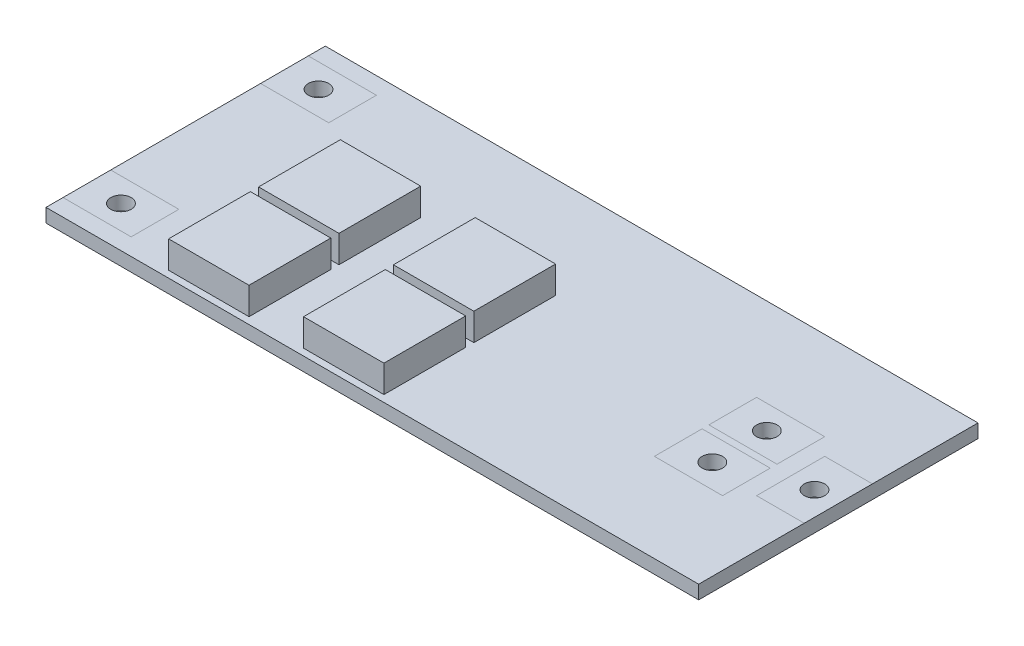
SolidWorks part; units mm, degrees
ref_plane "Alzado" through (0, 0, 0) normal (0, 0, 1) x (1, 0, 0)
ref_plane "Planta" through (0, 0, 0) normal (0, 1, 0) x (1, 0, 0)
ref_plane "Vista lateral" through (0, 0, 0) normal (1, 0, 0) x (0, 0, -1)
sketch "Croquis1" plane through (0, 0, 0) normal (0, 1, 0) x (1, 0, 0)
  line L0 (23.95, 0) -> (-23.95, 0) construction
  line L1 (-23.95, 10.25) -> (23.95, 10.25)
  line L2 (-23.95, 10.25) -> (-23.95, -10.25)
  line L3 (-23.95, -10.25) -> (23.95, -10.25)
  line L4 (23.95, 10.25) -> (23.95, -10.25)
  line L5 (-23.95, 10.25) -> (23.95, -10.25) construction
  line L6 (-23.95, -10.25) -> (23.95, 10.25) construction
  circle A0 centre (22.2, 0) radius 0.75
  circle A1 centre (16.7, 2) radius 0.75
  circle A2 centre (-21.45, 7.25) radius 0.75
  circle A3 centre (16.7, -2) radius 0.75
  circle A4 centre (-21.45, -7.25) radius 0.75
  point P0 (0, 0)
  point P10 (22.95, 0)
  point P13 (0, 0)
  dimension "D4" = 1.5
  dimension "D1" = 47.9
  dimension "D2" = 20.5
  dimension "D3" = 1
  dimension "D5" = 5.5
  dimension "D6" = 2
  dimension "D7" = 2.5
  dimension "D8" = 3
extrude "Saliente-Extruir1" add sketch "Croquis1" along normal blind 1
sketch "Croquis2" plane through (0, 1, 0) normal (0, 1, 0) x (1, 0, 0)
  line L0 (-7.55, -10.25) -> (-7.55, 10.25) construction
  line L1 (-15.45, 2.85) -> (-9.55, 2.85)
  line L2 (-15.45, 2.85) -> (-15.45, -3.15)
  line L3 (-15.45, -3.15) -> (-9.55, -3.15)
  line L4 (-9.55, 2.85) -> (-9.55, -3.15)
  line L5 (-15.45, -3.75) -> (-9.55, -3.75)
  line L6 (-15.45, -3.75) -> (-15.45, -9.75)
  line L7 (-15.45, -9.75) -> (-9.55, -9.75)
  line L8 (-9.55, -3.75) -> (-9.55, -9.75)
  line L9 (-23.95, -10.25) -> (23.95, -10.25) construction
  line L10 (23.95, 10.25) -> (-23.95, 10.25) construction
  line L11 (-23.95, 10.25) -> (-23.95, -10.25) construction
  line L12 (0.35, -9.75) -> (-5.55, -9.75)
  line L13 (-5.55, -3.75) -> (-5.55, -9.75)
  line L14 (0.35, -3.75) -> (-5.55, -3.75)
  line L15 (0.35, -3.75) -> (0.35, -9.75)
  line L16 (0.35, -3.15) -> (-5.55, -3.15)
  line L17 (-5.55, 2.85) -> (-5.55, -3.15)
  line L18 (0.35, 2.85) -> (-5.55, 2.85)
  line L19 (0.35, 2.85) -> (0.35, -3.15)
  point P14 (-12.2677, 2.5731)
  dimension "D1" = 5.9
  dimension "D2" = 6
  dimension "D3" = 0.6
  dimension "D4" = 0.5
  dimension "D5" = 8.5
  dimension "D6" = 2
extrude "Saliente-Extruir2" add sketch "Croquis2" along normal blind 2 separate body
sketch "Croquis3" plane through (0, 1, 0) normal (0, 1, 0) x (1, 0, 0)
  line L0 (23.95, 0) -> (-23.95, 0) construction
  line L1 (-23.95, 10.25) -> (-23.95, -10.25) construction
  line L2 (23.95, -10.25) -> (23.95, 10.25) construction
  line L3 (-18.95, 5.5) -> (-23.95, 5.5)
  line L4 (-18.95, 5.5) -> (-18.95, 9)
  line L5 (-18.95, 9) -> (-23.95, 9)
  line L6 (-23.95, 5.5) -> (-23.95, 9)
  line L7 (-18.95, 5.5) -> (-23.95, 9) construction
  line L8 (-18.95, 9) -> (-23.95, 5.5) construction
  line L9 (14.2, 3.75) -> (19.2, 3.75)
  line L10 (14.2, 3.75) -> (14.2, 0.25)
  line L11 (14.2, 0.25) -> (19.2, 0.25)
  line L12 (19.2, 3.75) -> (19.2, 0.25)
  line L13 (14.2, 3.75) -> (19.2, 0.25) construction
  line L14 (14.2, 0.25) -> (19.2, 3.75) construction
  line L15 (23.95, -2.5) -> (20.45, -2.5)
  line L16 (23.95, -2.5) -> (23.95, 2.5)
  line L17 (23.95, 2.5) -> (20.45, 2.5)
  line L18 (20.45, -2.5) -> (20.45, 2.5)
  line L19 (23.95, -2.5) -> (20.45, 2.5) construction
  line L20 (23.95, 2.5) -> (20.45, -2.5) construction
  line L21 (14.2, -0.25) -> (19.2, -0.25)
  line L22 (19.2, -3.75) -> (19.2, -0.25)
  line L23 (14.2, -3.75) -> (19.2, -3.75)
  line L24 (14.2, -3.75) -> (14.2, -0.25)
  line L25 (-18.95, -9) -> (-23.95, -9)
  line L26 (-23.95, -5.5) -> (-23.95, -9)
  line L27 (-18.95, -5.5) -> (-23.95, -5.5)
  line L28 (-18.95, -5.5) -> (-18.95, -9)
  point P0 (-21.45, 7.25)
  point P6 (0, 0)
  point P12 (16.7, 2)
  point P18 (22.2, 0)
  point P24 (23.95, 2.5)
  dimension "D1" = 3.5
split line "Línea de partición1"
